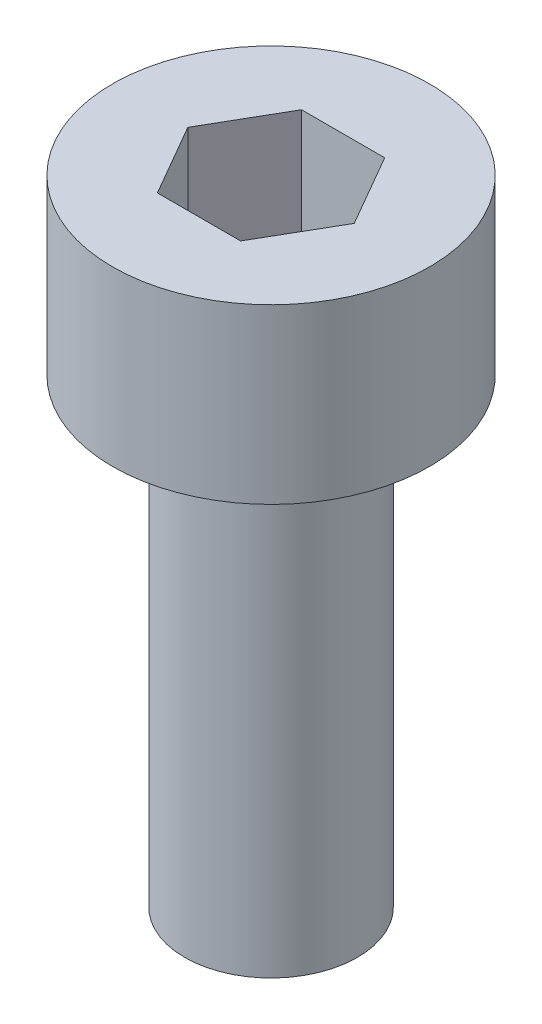
SolidWorks part; units mm, degrees
material "AISI 304"
ref_plane "Front Plane" through (0, 0, 0) normal (0, 0, 1) x (1, 0, 0)
ref_plane "Top Plane" through (0, 0, 0) normal (0, 1, 0) x (1, 0, 0)
ref_plane "Right Plane" through (0, 0, 0) normal (1, 0, 0) x (0, 0, -1)
sketch "Sketch1" plane through (0, 0, 0) normal (0, 0, 1) x (1, 0, 0)
  line L0 (0, 61.6916) -> (0, -59.3578) construction
  line L1 (0, -8) -> (1.5, -8)
  line L2 (1.5, -8) -> (1.5, 0)
  line L3 (1.5, 0) -> (2.75, 0)
  line L4 (2.75, 0) -> (2.75, 3)
  line L5 (2.75, 3) -> (0, 3)
  line L6 (0, 3) -> (0, -8)
  dimension "D1" = 8
  dimension "D2" = 5.5
  dimension "D3" = 3
  dimension "D4" = 3
revolve "Revolve1" add sketch "Sketch1" angle 360 about L0
sketch "Sketch2" plane through (0, 3, 0) normal (0, 1, 0) x (-1, 0, 0)
  line L1 (-0.7217, -1.25) -> (0.7217, -1.25)
  line L2 (0.7217, -1.25) -> (1.4434, 0)
  line L3 (1.4434, 0) -> (0.7217, 1.25)
  line L4 (0.7217, 1.25) -> (-0.7217, 1.25)
  line L5 (-0.7217, 1.25) -> (-1.4434, 0)
  line L6 (-1.4434, 0) -> (-0.7217, -1.25)
  circle A0 centre (0, 0) radius 1.25 construction
  dimension "D1" = 2.5
extrude "Cut-Extrude1" cut sketch "Sketch2" against normal blind 2.5
